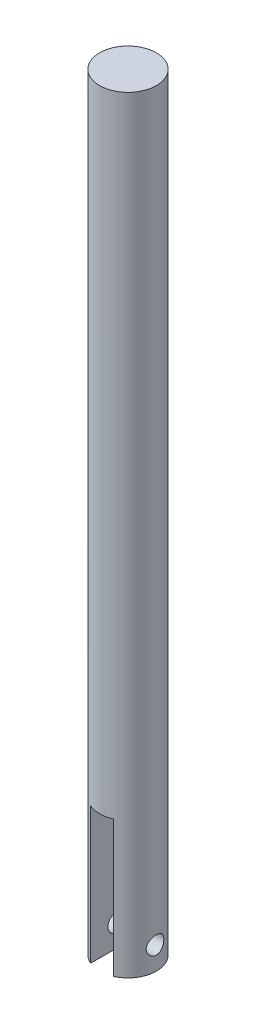
SolidWorks part; units mm, degrees
ref_plane "Front Plane" through (0, 0, 0) normal (0, 0, 1) x (1, 0, 0)
ref_plane "Top Plane" through (0, 0, 0) normal (0, 1, 0) x (1, 0, 0)
ref_plane "Right Plane" through (0, 0, 0) normal (1, 0, 0) x (0, 0, -1)
sketch "Sketch1" plane through (0, 0, 0) normal (0, 1, 0) x (1, 0, 0)
  circle A0 centre (0, 0) radius 5
  dimension "D1" = 10
extrude "Boss-Extrude1" add sketch "Sketch1" along normal mid plane 135
sketch "Sketch2" plane through (0, 0, 0) normal (0, 0, 1) x (1, 0, 0)
  line L0 (-5, -67.5) -> (5, -67.5) construction
  line L1 (-2, -67.5) -> (2, -67.5)
  line L2 (-2, -67.5) -> (-2, -43.5)
  line L3 (-2, -43.5) -> (2, -43.5)
  line L4 (2, -67.5) -> (2, -43.5)
  point P6 (0, -67.5)
  dimension "D1" = 24
  dimension "D2" = 4
extrude "Cut-Extrude1" cut sketch "Sketch2" against normal through all both and the other way through all
sketch "Sketch3" plane through (0, 0, 0) normal (1, 0, 0) x (0, 0, -1)
  line L0 (-4.5826, -67.5) -> (4.5826, -67.5) construction
  circle A0 centre (0, -63.5) radius 1.55
  dimension "D1" = 3.1
  dimension "D2" = 4
extrude "Cut-Extrude2" cut sketch "Sketch3" against normal through all both and the other way through all
equation "\"ScrewSize\"= 3.1mm"
